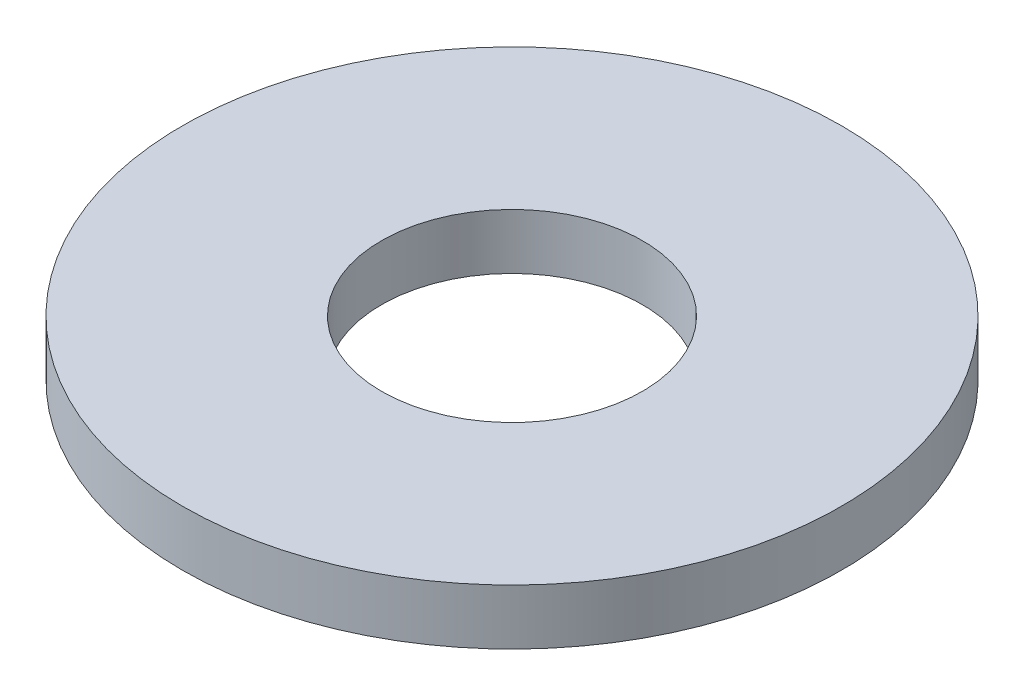
SolidWorks part; units mm, degrees
ref_plane "正面" through (0, 0, 0) normal (0, 0, 1) x (1, 0, 0)
ref_plane "平面" through (0, 0, 0) normal (0, 1, 0) x (1, 0, 0)
ref_plane "右側面" through (0, 0, 0) normal (1, 0, 0) x (0, 0, -1)
sketch "ｽｹｯﾁ1" plane through (0, 0, 0) normal (0, 1, 0) x (1, 0, 0)
  circle A0 centre (0, 0) radius 5.05
  circle A1 centre (0, 0) radius 2
  dimension "D1" = 4
  dimension "D2" = 10.1
extrude "押し出し1" add sketch "ｽｹｯﾁ1" along normal blind 0.85
